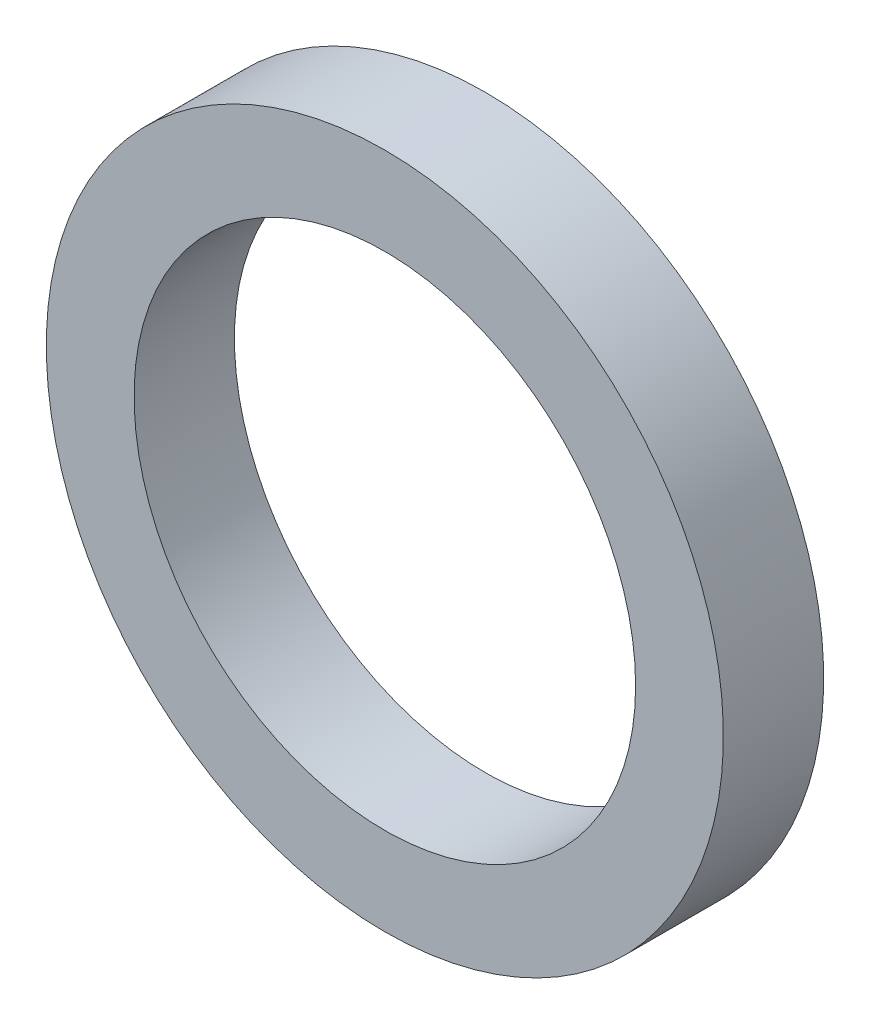
SolidWorks part; units mm, degrees
ref_plane "Front Plane" through (0, 0, 0) normal (1, 0, 0) x (0, 1, 0)
ref_plane "Top Plane" through (0, 0, 0) normal (0, 0, 1) x (0, 1, 0)
ref_plane "Right Plane" through (0, 0, 0) normal (0, 1, 0) x (-1, 0, 0)
sketch "Sketch1" plane through (0, 0, 0) normal (0, 0, 1) x (0, 1, 0)
  circle A0 centre (0, 0) radius 10
  dimension "D1" = 20
extrude "Extrude-Thin1" add sketch "Sketch1" along normal blind 4 thin
